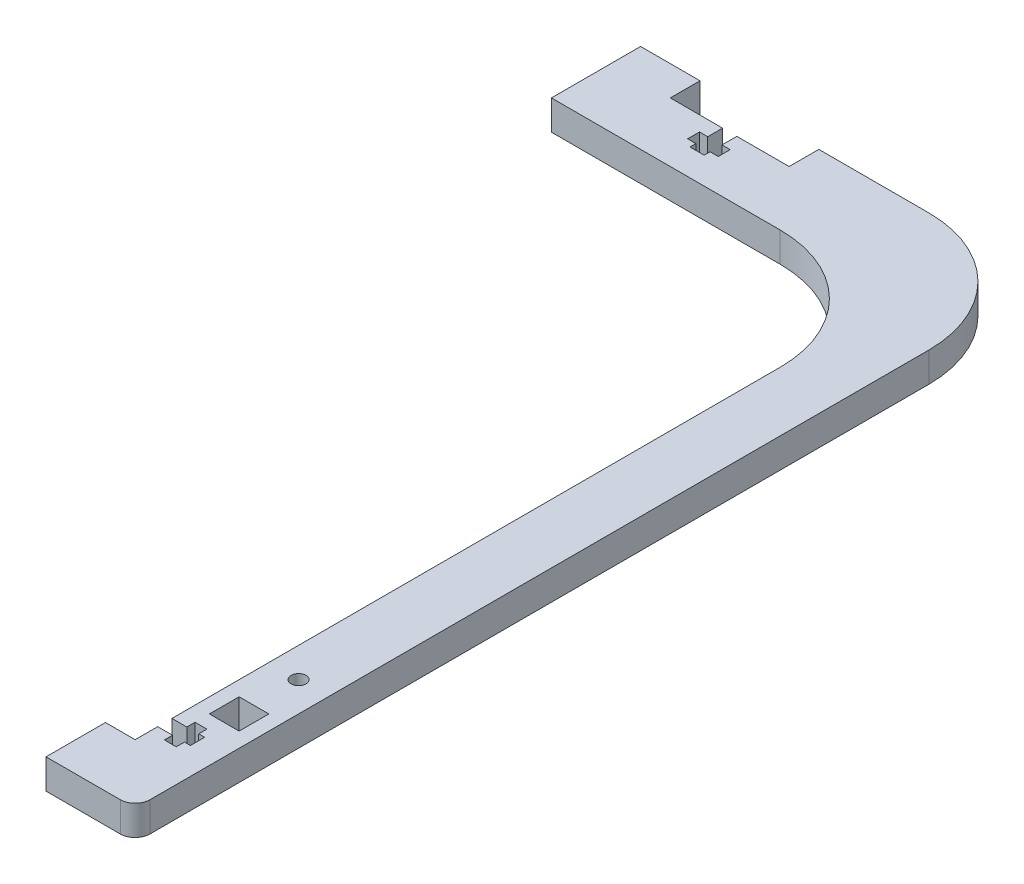
SolidWorks part; units mm, degrees
material "6061 Alloy"
ref_plane "Front Plane" through (0, 0, 0) normal (0, 0, 1) x (1, 0, 0)
ref_plane "Top Plane" through (0, 0, 0) normal (0, 1, 0) x (1, 0, 0)
ref_plane "Right Plane" through (0, 0, 0) normal (1, 0, 0) x (0, 0, -1)
sketch "Sketch1" plane through (0, 0, 0) normal (0, 1, 0) x (1, 0, 0)
  line L0 (44.3531, 10.8124) -> (44.3531, -114.3588)
  line L1 (44.3531, -114.3588) -> (44.3531, -119.1849)
  line L2 (51.3381, -122.2327) -> (50.0681, -122.2327)
  line L3 (50.0681, -122.2327) -> (50.0681, -123.9853)
  line L4 (50.0681, -123.9853) -> (47.5281, -123.9853)
  line L5 (47.5281, -123.9853) -> (47.5281, -122.2327)
  line L6 (47.5281, -122.2327) -> (44.3531, -122.2327)
  line L7 (51.3381, -119.1849) -> (50.0681, -119.1849)
  line L8 (50.0681, -119.1849) -> (50.0681, -117.4323)
  line L9 (50.0681, -117.4323) -> (47.5281, -117.4323)
  line L10 (47.5281, -117.4323) -> (47.5281, -119.1849)
  line L11 (47.5281, -119.1849) -> (44.3531, -119.1849)
  line L12 (44.3531, -127.0588) -> (38.0031, -127.0588)
  line L13 (38.0031, -127.0588) -> (38.0031, -139.7588)
  line L14 (38.0031, -139.7588) -> (44.3531, -139.7588)
  line L15 (44.3531, -139.7588) -> (53.8781, -139.7588)
  line L16 (57.0531, -136.5838) -> (57.0531, 29.8624)
  line L17 (-29.9419, 55.2624) -> (-29.9419, 36.2124)
  line L18 (-17.2419, 55.2624) -> (-17.2419, 48.9124)
  line L19 (-17.2419, 48.9124) -> (-6.0659, 48.9124)
  line L20 (-3.018, 48.9124) -> (8.1581, 48.9124)
  line L21 (8.1581, 48.9124) -> (8.1581, 55.2624)
  line L22 (-6.0659, 41.9274) -> (-6.0659, 43.1974)
  line L23 (-6.0659, 43.1974) -> (-7.8185, 43.1974)
  line L24 (-7.8185, 43.1974) -> (-7.8185, 45.7374)
  line L25 (-7.8185, 45.7374) -> (-6.0659, 45.7374)
  line L26 (-6.0659, 45.7374) -> (-6.0659, 48.9124)
  line L27 (-3.018, 41.9274) -> (-3.018, 43.1974)
  line L28 (-3.018, 43.1974) -> (-1.2654, 43.1974)
  line L29 (-1.2654, 43.1974) -> (-1.2654, 45.7374)
  line L30 (-1.2654, 45.7374) -> (-3.018, 45.7374)
  line L31 (-3.018, 45.7374) -> (-3.018, 48.9124)
  line L32 (8.1581, 55.2624) -> (31.6531, 55.2624)
  line L33 (50.7031, -114.3588) -> (47.5281, -114.3588)
  line L34 (47.5281, -114.3588) -> (47.5281, -108.0088)
  line L35 (47.5281, -108.0088) -> (53.8781, -108.0088)
  line L36 (53.8781, -108.0088) -> (53.8781, -114.3588)
  line L37 (53.8781, -114.3588) -> (50.7031, -114.3588)
  line L38 (-6.0659, 41.9274) -> (-3.018, 41.9274)
  line L39 (44.3531, -122.2327) -> (44.3531, -127.0588)
  line L40 (51.3381, -119.1849) -> (51.3381, -122.2327)
  line L41 (18.9531, 36.2124) -> (-29.9419, 36.2124)
  line L42 (-17.2419, 55.2624) -> (-29.9419, 55.2624)
  arc A0 (44.3531, 10.8124) -> (18.9531, 36.2124) centre (18.9531, 10.8124) ccw
  arc A1 (57.0531, 29.8624) -> (31.6531, 55.2624) centre (31.6531, 29.8624) ccw
  arc A2 (53.8781, -139.7588) -> (57.0531, -136.5838) centre (53.8781, -136.5838) ccw
  circle A3 centre (50.7031, -98.4838) radius 1.5875
extrude "Boss-Extrude1" add sketch "Sketch1" along normal blind 6.35
